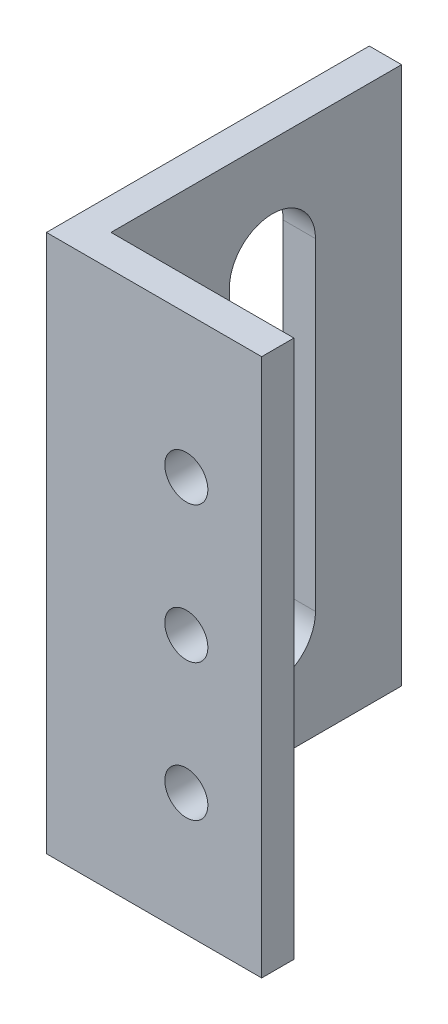
SolidWorks part; units mm, degrees
ref_plane "前视基准面" through (0, 0, 0) normal (0, 0, 1) x (1, 0, 0)
ref_plane "上视基准面" through (0, 0, 0) normal (0, 1, 0) x (1, 0, 0)
ref_plane "右视基准面" through (0, 0, 0) normal (1, 0, 0) x (0, 0, -1)
sketch "草图1" plane through (0, 0, 0) normal (0, 1, 0) x (1, 0, 0)
  line L2 (-1.5, 15) -> (1.5, 15)
  line L3 (-1.5, 15) -> (-1.5, -15)
  line L4 (-1.5, -15) -> (1.5, -15)
  line L5 (1.5, 15) -> (1.5, -15)
  line L6 (-1.5, 15) -> (1.5, -15) construction
  line L7 (-1.5, -15) -> (1.5, 15) construction
  line L8 (-1.5, -15) -> (18.5, -15)
  line L9 (-1.5, -15) -> (-1.5, -12)
  line L10 (-1.5, -12) -> (18.5, -12)
  line L11 (18.5, -15) -> (18.5, -12)
  point P2 (0, 0)
  dimension "D1" = 3
  dimension "D2" = 3
  dimension "D3" = 30
  dimension "D4" = 20
extrude "凸台-拉伸1" add sketch "草图1" along normal blind 50 contours L3 L10 L5 L2 | L10 L3 L4 L5 | L8 L11 L10 L5
sketch "草图2" plane through (0, 0, 15) normal (0, 0, 1) x (1, 0, 0)
  line L0 (11.5, 50) -> (11.5, 0) construction
  line L1 (-1.5, 50) -> (18.5, 50) construction
  line L3 (18.5, 50) -> (18.5, 0) construction
  circle A0 centre (11.5, 36.8) radius 2
  circle A2 centre (11.5, 24.1) radius 2
  circle A3 centre (11.5, 11.4) radius 2
  dimension "D1" = 4
  dimension "D2" = 13.2
  dimension "D4" = 12.7
  dimension "D5" = 7
  dimension "D3" = 3
extrude "切除-拉伸1" cut sketch "草图2" against normal blind 10
sketch "草图3" plane through (-1.5, 0, 0) normal (-1, 0, 0) x (0, 0, 1)
  line L0 (-3, 40) -> (-3, 10) construction
  line L1 (1, 40) -> (1, 10)
  line L2 (-7, 40) -> (-7, 10)
  line L4 (-15, 50) -> (-15, 0) construction
  line L5 (-15, 25) -> (15, 25) construction
  line L6 (15, 50) -> (15, 0) construction
  arc A0 (1, 40) -> (-7, 40) centre (-3, 40) ccw
  arc A1 (-7, 10) -> (1, 10) centre (-3, 10) ccw
  point P3 (-3, 25)
  dimension "D3" = 4
  dimension "D1" = 30
  dimension "D2" = 12
extrude "切除-拉伸2" cut sketch "草图3" against normal blind 10
